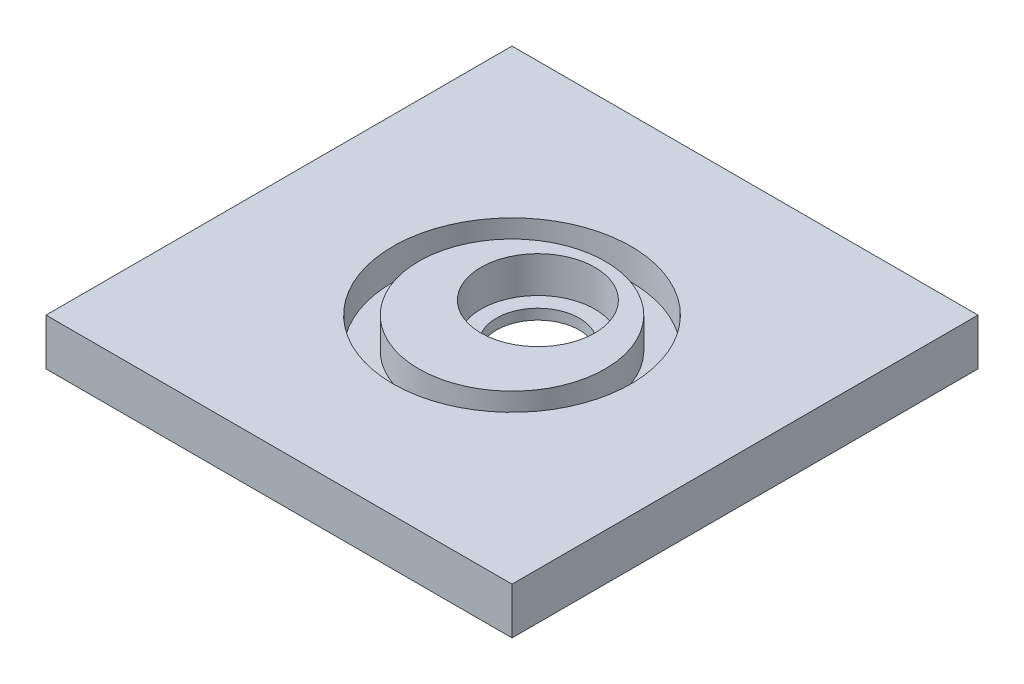
SolidWorks part; units mm, degrees
ref_plane "前视基准面" through (0, 0, 0) normal (0, 0, 1) x (1, 0, 0)
ref_plane "上视基准面" through (0, 0, 0) normal (0, 1, 0) x (1, 0, 0)
ref_plane "右视基准面" through (0, 0, 0) normal (1, 0, 0) x (0, 0, -1)
sketch "草图1" plane through (0, 0, 0) normal (0, 1, 0) x (1, 0, 0)
  line L1 (-22.5, -22.5) -> (22.5, -22.5)
  line L2 (-22.5, -22.5) -> (-22.5, 22.5)
  line L3 (-22.5, 22.5) -> (22.5, 22.5)
  line L4 (22.5, -22.5) -> (22.5, 22.5)
  line L5 (-22.5, -22.5) -> (22.5, 22.5) construction
  line L6 (-22.5, 22.5) -> (22.5, -22.5) construction
  point P0 (0, 0)
  dimension "D1" = 45
  dimension "D2" = 45
extrude "凸台-拉伸1" add sketch "草图1" along normal blind 4.5
sketch "草图2" plane through (0, 4.5, 0) normal (0, 1, 0) x (1, 0, 0)
  line L0 (0, 0) -> (0, 2.5) construction
  circle A0 centre (0, 2.5) radius 5.5
  dimension "D2" = 11
  dimension "D1" = 2.5
extrude "切除-拉伸1" cut sketch "草图2" against normal blind 3.5
sketch "草图3" plane through (0, 1, 0) normal (0, 1, 0) x (1, 0, 0)
  circle A0 centre (0, 2.5) radius 4
  dimension "D1" = 8
extrude "切除-拉伸2" cut sketch "草图3" against normal through all
sketch "草图4" plane through (0, 4.5, 0) normal (0, 1, 0) x (1, 0, 0)
  circle A0 centre (0, 0) radius 9
  circle A1 centre (0, 0) radius 11.5
  dimension "D1" = 18
  dimension "D2" = 23
extrude "切除-拉伸3" cut sketch "草图4" against normal blind 3
